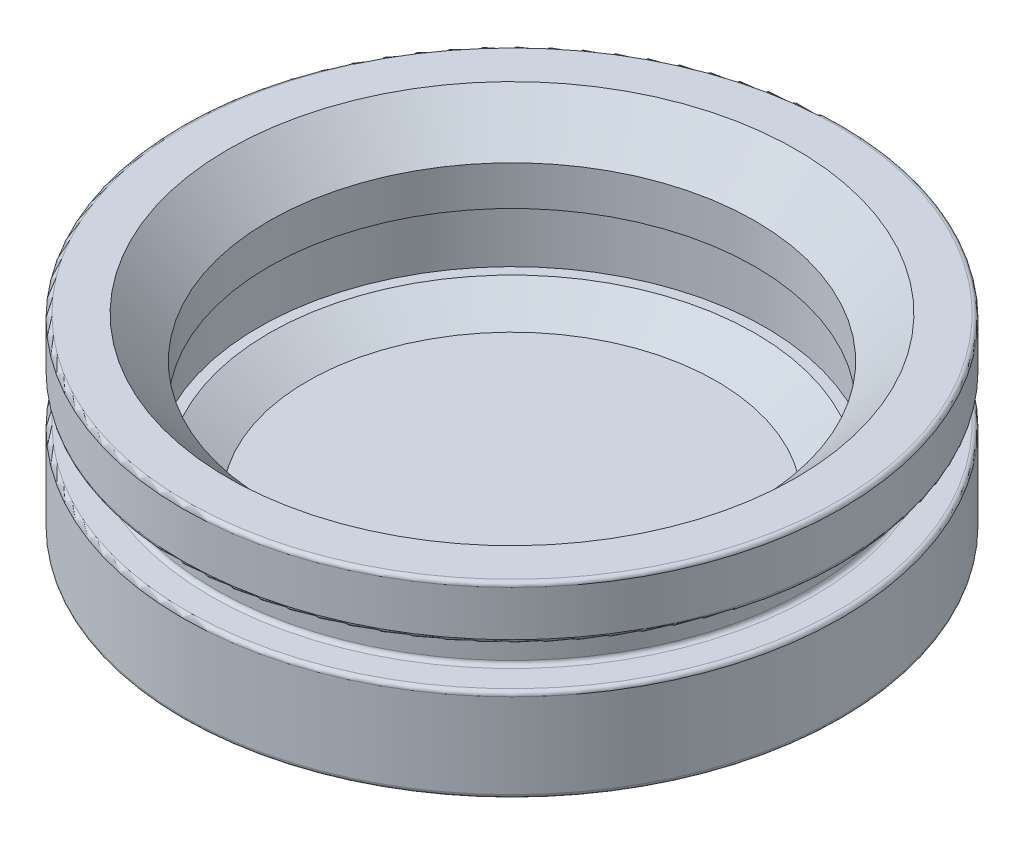
SolidWorks part; units mm, degrees
ref_plane "Front" through (0, 0, 0) normal (0, 0, 1) x (1, 0, 0)
ref_plane "Top" through (0, 0, 0) normal (0, 1, 0) x (1, 0, 0)
ref_plane "Right" through (0, 0, 0) normal (1, 0, 0) x (0, 0, -1)
sketch "Sketch1" plane through (0, 0, 0) normal (0, 0, 1) x (1, 0, 0)
  line L0 (0, 0) -> (0, 59.5949) construction
  line L1 (0, 0) -> (10.16, 4.4174)
  line L2 (10.16, 4.4174) -> (10.16, 7.239)
  line L3 (10.16, 10.16) -> (7.493, 10.16)
  line L4 (7.493, 10.16) -> (7.493, 7.6708)
  line L5 (6.3052, 5.207) -> (0, 5.207)
  line L6 (0, 5.207) -> (0, 0)
  line L7 (7.493, 7.6708) -> (7.8105, 7.6708)
  line L8 (7.8105, 7.6708) -> (7.8105, 5.8928)
  line L9 (7.8105, 5.8928) -> (7.493, 5.8928)
  line L10 (7.493, 5.8928) -> (6.3052, 5.207)
  line L11 (10.16, 8.509) -> (9.144, 8.509)
  line L12 (9.144, 8.509) -> (9.144, 7.239)
  line L13 (9.144, 7.239) -> (10.16, 7.239)
  line L14 (10.16, 8.509) -> (10.16, 10.16)
  dimension "D1" = 14.986
  dimension "D2" = 20.32
  dimension "D3" = 4.953
  dimension "D4" = 66.501
  dimension "D5" = 10.16
  dimension "D6" = 2.4892
  dimension "D7" = 1.778
  dimension "D8" = 15.621
  dimension "D9" = 1.651
  dimension "D10" = 1.27
  dimension "D11" = 1.016
  dimension "D12" = 30
revolve "Revolve1" add sketch "Sketch1" angle 360 about L0
chamfer "Chamfer1" distance 1.27 angle 45 1 edges at (7.493, 10.16, 0)
fillet "Fillet1" radius 0.127 6 edges at (10.16, 10.16, 0) (10.16, 4.4174, 0) (10.16, 7.239, 0) (10.16, 8.509, 0) (9.144, 7.239, 0) (9.144, 8.509, 0)
